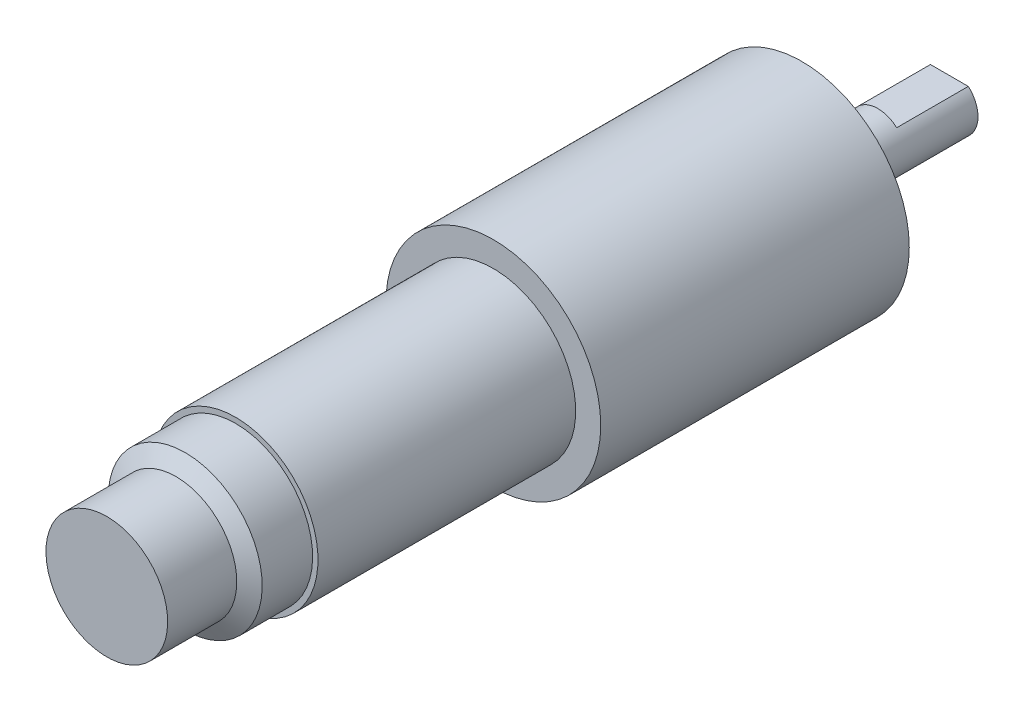
SolidWorks part; units mm, degrees
ref_plane "Front" through (0, 0, 0) normal (0, 0, 1) x (1, 0, 0)
ref_plane "Top" through (0, 0, 0) normal (0, 1, 0) x (1, 0, 0)
ref_plane "Right" through (0, 0, 0) normal (1, 0, 0) x (0, 0, -1)
sketch "Sketch1" plane through (0, 0, 0) normal (1, 0, 0) x (0, 0, -1)
  line L0 (0, 0) -> (31.5789, 0) construction
  line L1 (20.6, 0) -> (20.6, 4)
  line L2 (20.6, 4) -> (4, 4)
  line L3 (4, 4) -> (4, 9)
  line L4 (4, 9) -> (0, 9)
  line L5 (0, 9) -> (0, 15)
  line L6 (0, 15) -> (-43.1, 15)
  line L7 (-43.1, 15) -> (-43.1, 0)
  line L8 (-43.1, 0) -> (20.6, 0)
  dimension "D1" = 15
  dimension "D2" = 9
  dimension "D3" = 4
  dimension "D4" = 20.6
  dimension "D5" = 4
  dimension "D6" = 43.1
revolve "Revolve1" add sketch "Sketch1" angle 360 about L0
sketch "Sketch2" plane through (0, 0, -20.6) normal (0, 0, -1) x (-1, 0, 0)
  line L0 (-2.6458, 3) -> (2.6458, 3)
  circle A0 centre (0, 0) radius 4 construction
  circle A1 centre (0, 0) radius 4 construction
  arc A2 (2.6458, 3) -> (-2.6458, 3) centre (0, 0) ccw
  dimension "D1" = 3
extrude "Cut-Extrude1" cut sketch "Sketch2" against normal blind 10
sketch "Sketch3" plane through (0, 0, 0) normal (1, 0, 0) x (0, 0, -1)
  line L0 (-43.1, 11.5) -> (-79.1, 11.5)
  line L1 (-43.1, 15) -> (-43.1, -15) construction
  line L2 (-79.1, 11.5) -> (-79.1, 10.5)
  line L3 (-79.1, 10.5) -> (-85.1, 10.5)
  line L4 (0, 0) -> (-98.0339, 0) construction
  line L5 (-43.1, 11.5) -> (-43.1, 0)
  line L6 (-43.1, 0) -> (-93.9, 0)
  line L7 (-85.1, 4.5) -> (-85.1, 10.5)
  line L8 (-85.1, 4.5) -> (-86.6, 4.5)
  line L9 (-86.6, 4.5) -> (-86.6, 3)
  line L10 (-93.9, 1.5) -> (-88.2, 1.5)
  line L11 (-93.9, 1.5) -> (-93.9, 0)
  line L12 (-88.2, 1.5) -> (-88.2, 3)
  line L13 (-88.2, 3) -> (-86.6, 3)
  dimension "D1" = 85.1
  dimension "D2" = 11.5
  dimension "D3" = 10.5
  dimension "D4" = 6
  dimension "D5" = 4.5
  dimension "D6" = 1.5
  dimension "D7" = 8.8
  dimension "D8" = 3
  dimension "D9" = 1.5
  dimension "D10" = 5.7
revolve "Revolve2" add sketch "Sketch3" angle 360 about L4
sketch "Sketch4" plane through (0, 0, 0) normal (1, 0, 0) x (0, 0, -1)
  line L0 (-86.1461, 10.75) -> (-79.1, 10.75)
  line L1 (-79.1, 11.5) -> (-79.1, -11.5) construction
  line L2 (-79.1, 10.75) -> (-79.1, 0)
  line L3 (-79.1, 10.5) -> (-79.1, -10.5) construction
  line L4 (-85.1, 10.5) -> (-85.1, -10.5) construction
  line L8 (-79.1, 0) -> (-97.1, 0)
  line L9 (-97.1, 0) -> (-97.1, 8.5)
  line L10 (-97.1, 8.5) -> (-87.4451, 8.5)
  line L11 (-87.4451, 8.5) -> (-86.1461, 10.75)
  dimension "D1" = 120
  dimension "D2" = 10.75
  dimension "D3" = 12
  dimension "D4" = 8.5
revolve "Revolve3" add sketch "Sketch4" angle 360 about L8
sketch "Sketch5" plane through (0, 0, 0) normal (0, 0, -1) x (-1, 0, 0)
  line L0 (-13, 0) -> (13, 0) construction
  line L1 (0, 13) -> (0, -13) construction
  circle A0 centre (0, 0) radius 13 construction
  circle A1 centre (0, 13) radius 1.5
  circle A2 centre (13, 0) radius 1.5
  circle A3 centre (0, -13) radius 1.5
  circle A4 centre (-13, 0) radius 1.5
  dimension "D1" = 26
  dimension "D2" = 3
extrude "Cut-Extrude2" cut sketch "Sketch5" against normal blind 4
